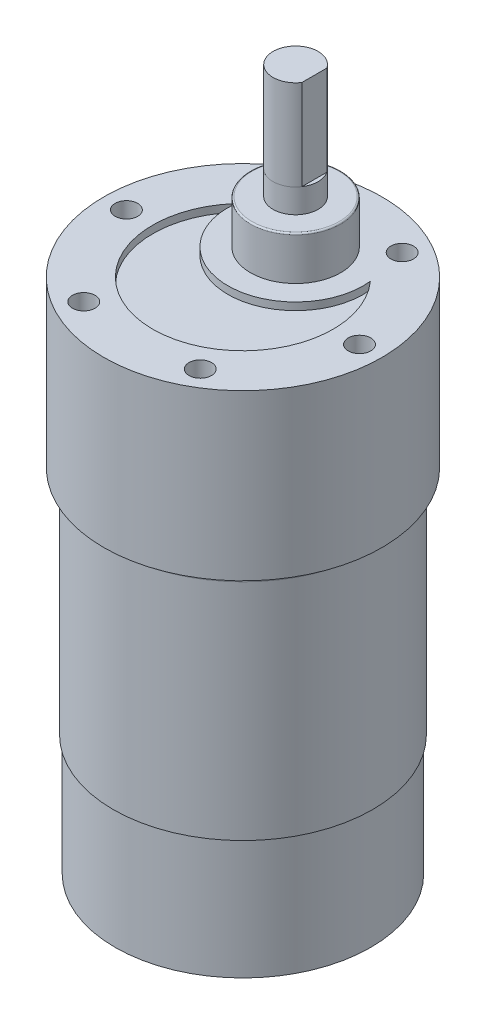
SolidWorks part; units mm, degrees
ref_plane "Alzado" through (0, 0, 0) normal (0, 0, 1) x (1, 0, 0)
ref_plane "Planta" through (0, 0, 0) normal (0, 1, 0) x (1, 0, 0)
ref_plane "Vista lateral" through (0, 0, 0) normal (1, 0, 0) x (0, 0, -1)
sketch "Croquis1" plane through (0, 0, 0) normal (0, 1, 0) x (1, 0, 0)
  circle A0 centre (0, 0) radius 17.25
  dimension "D1" = 34.5
extrude "Saliente-Extruir1" add sketch "Croquis1" along normal blind 30.8
fillet "Redondeo1" radius 1 1 edges at (0, 30.8, 17.25)
sketch "Croquis2" plane through (0, 30.8, 0) normal (0, 1, 0) x (1, 0, 0)
  circle A0 centre (0, 0) radius 18.5
  dimension "D1" = 37
extrude "Saliente-Extruir2" add sketch "Croquis2" along normal blind 21.9 separate body
sketch "Croquis3" plane through (0, 52.7, 0) normal (0, 1, 0) x (1, 0, 0)
  circle A0 centre (0, 7) radius 6
  dimension "D1" = 7
  dimension "D2" = 12
extrude "Saliente-Extruir3" add sketch "Croquis3" along normal blind 5.8 separate body
fillet "Redondeo2" radius 0.2 1 edges at (0, 58.5, -1)
sketch "Croquis4" plane through (0, 58.5, 0) normal (0, 1, 0) x (1, 0, 0)
  circle A0 centre (0, 7) radius 3
  dimension "D1" = 6
extrude "Saliente-Extruir4" add sketch "Croquis4" along normal blind 3.2 separate body
sketch "Croquis5" plane through (0, 61.7, 0) normal (0, 1, 0) x (1, 0, 0)
  line L0 (2.5, 8.6583) -> (2.5, 5.3417)
  arc A0 (2.5, 8.6583) -> (2.5, 5.3417) centre (0, 7) ccw
  dimension "D1" = 6
  dimension "D2" = 2.5
extrude "Saliente-Extruir5" add sketch "Croquis5" along normal blind 12 separate body
sketch "Croquis6" plane through (0, 52.7, 0) normal (0, 1, 0) x (1, 0, 0)
  line L0 (0, 0) -> (15.8622, 0) construction
  line L1 (0, 0) -> (7.75, 13.4234) construction
  line L2 (0, 0) -> (0, -15.5) construction
  circle A0 centre (0, 0) radius 15.5 construction
  circle A1 centre (15.5, 0) radius 1.5
  circle A2 centre (7.75, 13.4234) radius 1.5
  circle A3 centre (7.75, -13.4234) radius 1.5
  circle A4 centre (-7.75, -13.4234) radius 1.5
  circle A5 centre (-15.5, 0) radius 1.5
  circle A6 centre (-7.75, 13.4234) radius 1.5
  dimension "D1" = 31
  dimension "D2" = 3
  dimension "D3" = 60
extrude "Cortar-Extruir1" cut sketch "Croquis6" against normal blind 3
sketch "Croquis7" plane through (0, 0, 0) normal (0, -1, 0) x (1, 0, 0)
  circle A0 centre (0, 0) radius 17
  dimension "D1" = 34
extrude "Saliente-Extruir6" add sketch "Croquis7" along normal blind 16 separate body
sketch "Croquis8" plane through (0, 52.7, 0) normal (0, 1, 0) x (1, 0, 0)
  arc A0 (-8.9443, 8) -> (8.9443, 8) centre (0, 0) ccw
  arc A1 (-8.9443, 8) -> (8.9443, 8) centre (0, 7) ccw
  dimension "D1" = 24
  dimension "D2" = 18
extrude "Cortar-Extruir2" cut sketch "Croquis8" against normal blind 1
